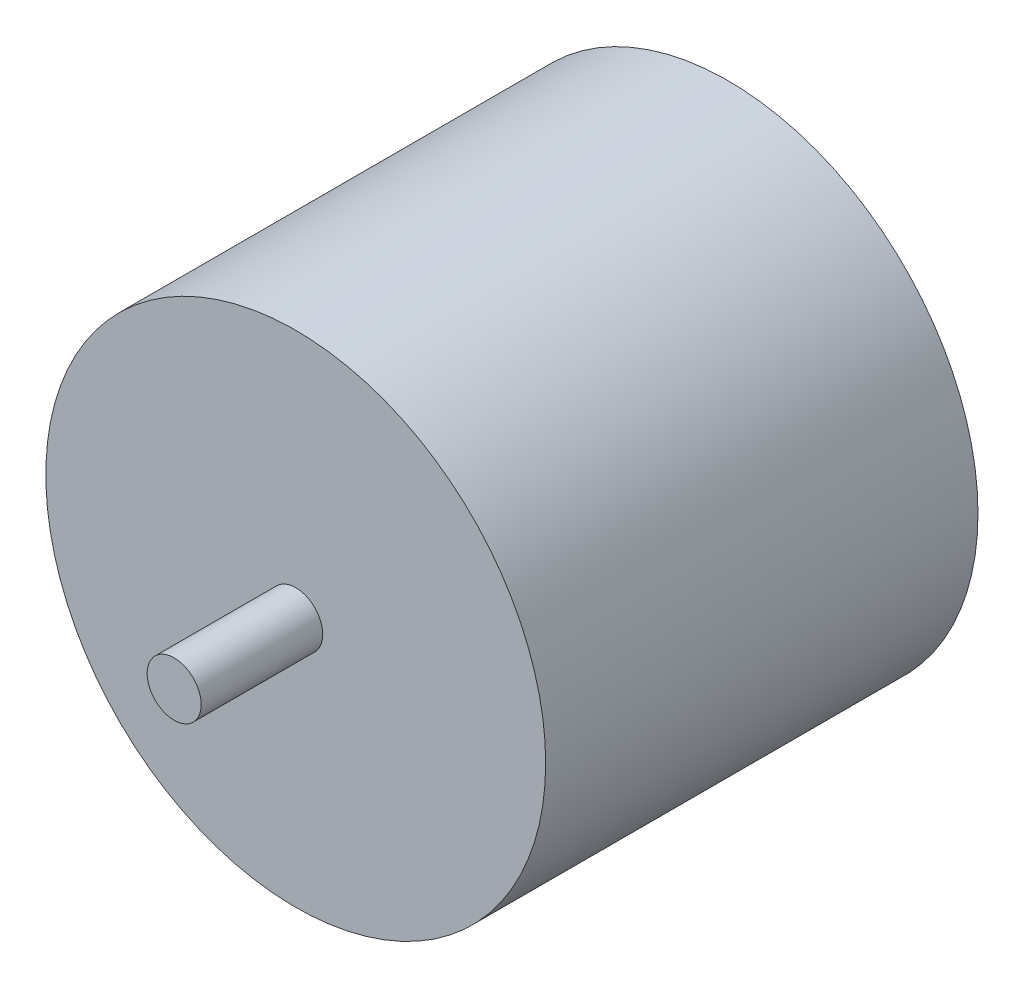
SolidWorks part; units mm, degrees
ref_plane "Front Plane" through (0, 0, 0) normal (0, 0, 1) x (1, 0, 0)
ref_plane "Top Plane" through (0, 0, 0) normal (0, 1, 0) x (1, 0, 0)
ref_plane "Right Plane" through (0, 0, 0) normal (1, 0, 0) x (0, 0, -1)
sketch "Sketch2" plane through (0, 0, 0) normal (0, 0, 1) x (1, 0, 0)
  circle A0 centre (0, 0) radius 18.5
  dimension "D1" = 37
extrude "Boss-Extrude1" add sketch "Sketch2" against normal blind 32
sketch "Sketch3" plane through (0, 0, 0) normal (0, 0, 1) x (1, 0, 0)
  circle A0 centre (0, 0) radius 2
  dimension "D1" = 4
extrude "Boss-Extrude3" add sketch "Sketch3" along normal blind 9 contours A0
